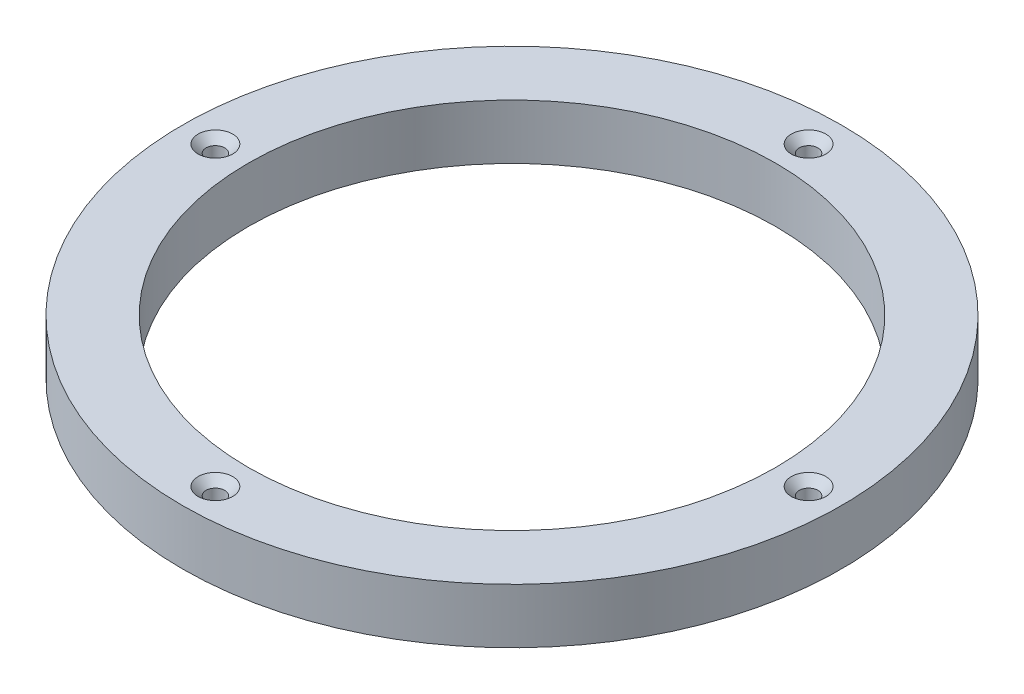
SolidWorks part; units mm, degrees
ref_plane "Piano frontale" through (0, 0, 0) normal (0, 0, 1) x (1, 0, 0)
ref_plane "Piano superiore" through (0, 0, 0) normal (0, 1, 0) x (1, 0, 0)
ref_plane "Piano destro" through (0, 0, 0) normal (1, 0, 0) x (0, 0, -1)
sketch "Schizzo1" plane through (0, 0, 0) normal (0, 1, 0) x (1, 0, 0)
  circle A0 centre (0, 0) radius 60
  circle A1 centre (0, 0) radius 48
  dimension "D1" = 120
  dimension "D2" = 12
extrude "Estrusione-Estrusione1" add sketch "Schizzo1" along normal blind 10
hole_wizard "Foro svasato per Vite M3-1" positions "Schizzo3D1" profile "Schizzo2" countersink size "M3" standard "ISO"
sketch3d "Schizzo3D1"
  line L0 (0, 10, 54) -> (0, 10, -54) construction
  line L2 (-54, 10, 0) -> (54, 10, 0) construction
  line L4 (0, 0, 0) -> (0, 10, 0) construction
  point P0 (0, 10, 54)
  point P2 (54, 10, 0)
  point P4 (0, 10, -54)
  point P6 (-54, 10, 0)
  dimension "D1" = 54
  dimension "D2" = 54
  dimension "D3" = 54
  dimension "D4" = 54
sketch "Schizzo2" plane through (0, 10, 54) normal (1, 0, 0) x (0, 0, 1)
  line L0 (0, 0) -> (0, 189.0215)
  line L1 (0, 189.0215) -> (1.7, 188)
  line L2 (1.7, 188) -> (1.7, 1.45)
  line L3 (1.7, 1.45) -> (3.15, 0)
  line L5 (3.15, 0) -> (0, 0)
  line L6 (-1.7, 1.45) -> (-3.15, 0) construction
  line L10 (0, 189.0215) -> (-1.7, 188) construction
  line L11 (0, -6.35) -> (0, 107.95) construction
  dimension "Hole Dia." = 3.4
  dimension "Hole Depth" = 188
  dimension "Near C'Sink Dia." = 6.3
  dimension "Near C'Sink Angle" = 90
  dimension "Drill Angle" = 118
